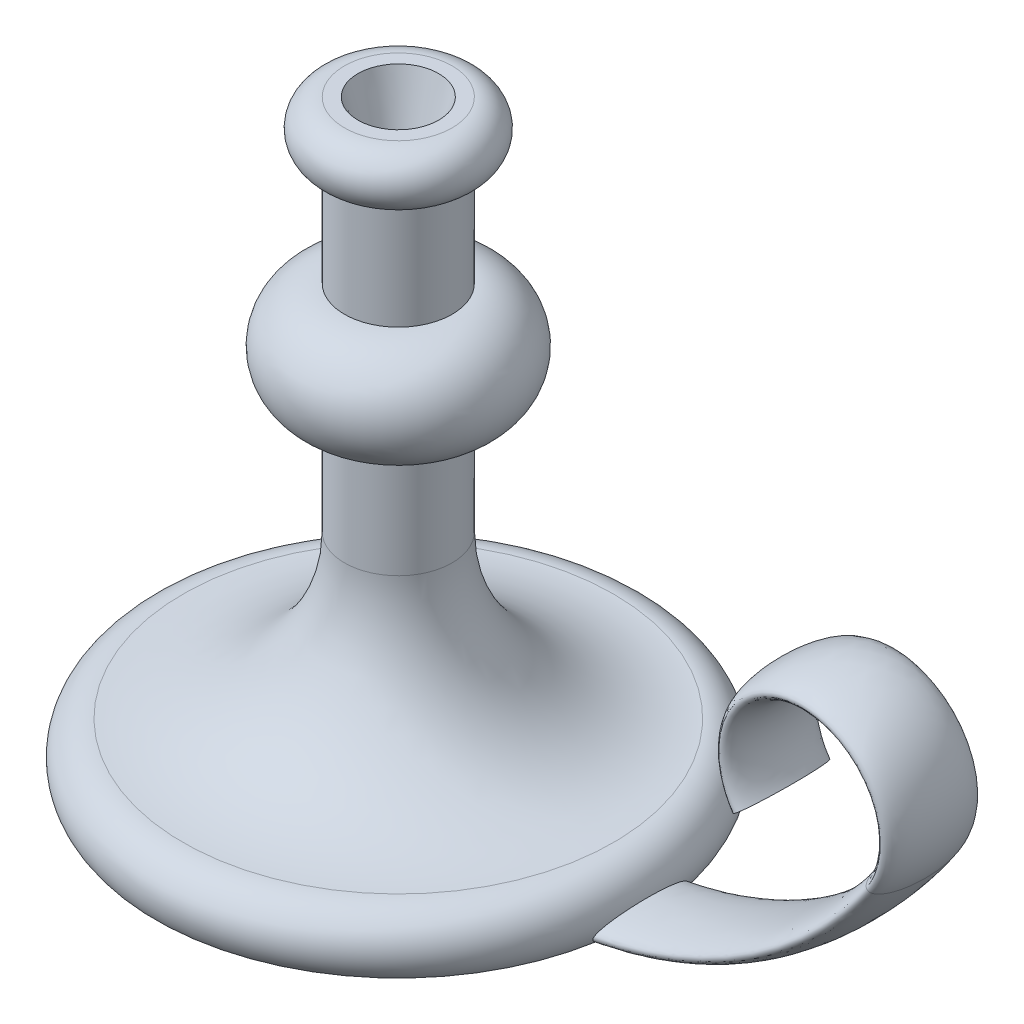
SolidWorks part; units mm, degrees
ref_plane "Front Plane" through (0, 0, 0) normal (0, 0, 1) x (1, 0, 0)
ref_plane "Top Plane" through (0, 0, 0) normal (0, 1, 0) x (1, 0, 0)
ref_plane "Right Plane" through (0, 0, 0) normal (1, 0, 0) x (0, 0, -1)
sketch "Sketch1" plane through (0, 0, 0) normal (0, 0, 1) x (1, 0, 0)
  line L0 (0, 0) -> (0, 220)
  line L1 (0, 220) -> (20, 220)
  line L2 (0, 0) -> (90, 0)
  line L3 (20, 200) -> (20, 160)
  line L4 (20, 120) -> (20, 80)
  arc A0 (20, 220) -> (20, 200) centre (20, 210) cw
  arc A1 (20, 160) -> (20, 120) centre (20, 140) cw
  arc A2 (20, 80) -> (80, 20) centre (80, 80) ccw
  arc A3 (80, 20) -> (90, 0) centre (80, 7.5) cw
  dimension "D4" = 10
  dimension "D6" = 20
  dimension "D5" = 60
  dimension "D1" = 90
  dimension "D2" = 220
  dimension "D3" = 20
  dimension "D7" = 40
  dimension "D8" = 80
revolve "Revolve1" add sketch "Sketch1" angle 360 about L0
sketch "Sketch2" plane through (0, 0, 0) normal (0, 0, 1) x (1, 0, 0)
  line L0 (0, 10) -> (60, 10)
  line L1 (0, 227.4356) -> (0, 175.1288) construction
  line L2 (0, 200) -> (0, 160) construction
  arc A0 (60, 10) -> (183.5921, 75) centre (60, 160) ccw
  arc A1 (183.5921, 75) -> (150.6342, 75) centre (167.1131, 86.3333) ccw
  dimension "D3" = 150
  dimension "D4" = 20
  dimension "D1" = 60
  dimension "D2" = 65
  dimension "D5" = 10
sketch "Sketch3" plane through (0, 0, 0) normal (1, 0, 0) x (0, 0, -1)
  ellipse E0 centre (0, 0) end of major axis (-17.5, 0) minor radius 5
  dimension "D1" = 35
  dimension "D2" = 10
sweep "Sweep1" add profiles "Sketch3" path "Sketch2"
sketch "Sketch4" plane through (0, 220, 0) normal (0, 1, 0) x (1, 0, 0)
  circle A0 centre (0, 0) radius 15
  dimension "D1" = 30
extrude "Cut-Extrude1" cut sketch "Sketch4" against normal blind 25 draft 15
